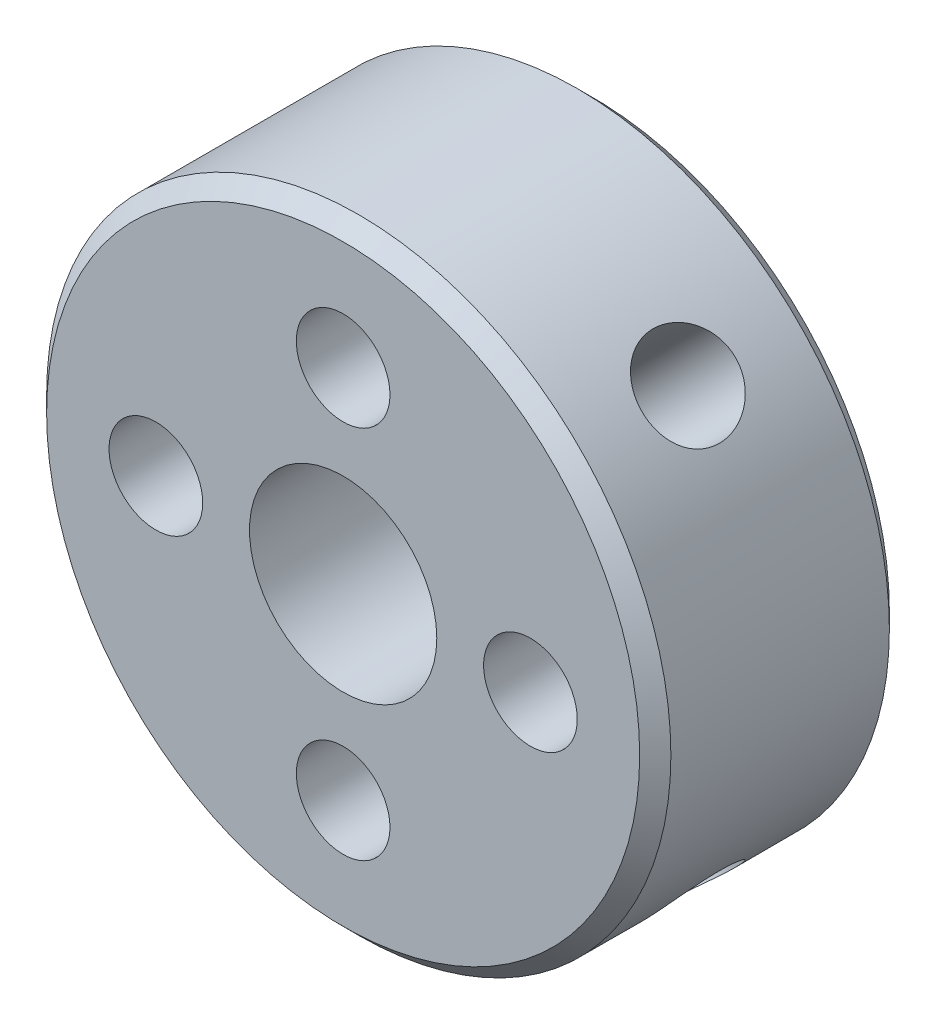
SolidWorks part; units mm, degrees
ref_plane "正面" through (0, 0, 0) normal (0, 0, 1) x (1, 0, 0)
ref_plane "平面" through (0, 0, 0) normal (0, 1, 0) x (1, 0, 0)
ref_plane "右側面" through (0, 0, 0) normal (1, 0, 0) x (0, 0, -1)
sketch "ｽｹｯﾁ1" plane through (0, 0, 0) normal (0, 0, 1) x (1, 0, 0)
  line L0 (-6, 0) -> (0, 0) construction
  line L1 (0, 0) -> (6, 0) construction
  line L2 (0, 6) -> (0, -6) construction
  circle A0 centre (0, 0) radius 10
  circle A1 centre (0, 0) radius 3
  circle A2 centre (-6, 0) radius 1.5
  circle A3 centre (6, 0) radius 1.5
  circle A4 centre (0, 6) radius 1.5
  circle A5 centre (0, -6) radius 1.5
  dimension "D1" = 6
  dimension "D2" = 20
  dimension "D3" = 3
  dimension "D5" = 12
  dimension "D4" = 12
extrude "ﾎﾞｽ - 押し出し1" add sketch "ｽｹｯﾁ1" along normal blind 8
ref_plane "平面1" through (0, 0, 0) normal (0.7071, 0.7071, 0) x (0.7071, -0.7071, 0)
ref_plane "平面2" through (0, 0, 0) normal (-0.7071, 0.7071, 0) x (0.7071, 0.7071, 0)
sketch "ｽｹｯﾁ2" plane through (0, 0, 0) normal (0.7071, 0.7071, 0) x (0.7071, -0.7071, 0)
  line L0 (0, 55) -> (0, -55) construction
  line L1 (3, 0) -> (-3, 0) construction
  circle A0 centre (0, -4) radius 1.5
  dimension "D1" = 4
  dimension "D2" = 3
extrude "ｶｯﾄ - 押し出し1" cut sketch "ｽｹｯﾁ2" along normal up to next
sketch "ｽｹｯﾁ3" plane through (0, 0, 0) normal (-0.7071, 0.7071, 0) x (0.7071, 0.7071, 0)
  line L0 (0, -55) -> (0, 55) construction
  line L1 (3, 0) -> (-3, 0) construction
  circle A0 centre (0, -4) radius 1.5
  dimension "D1" = 3
  dimension "D2" = 4
extrude "ｶｯﾄ - 押し出し2" cut sketch "ｽｹｯﾁ3" against normal up to next
chamfer "面取り1" distance 0.5 angle 45 2 edges at (10, 0, 0) (10, 0, 8)
